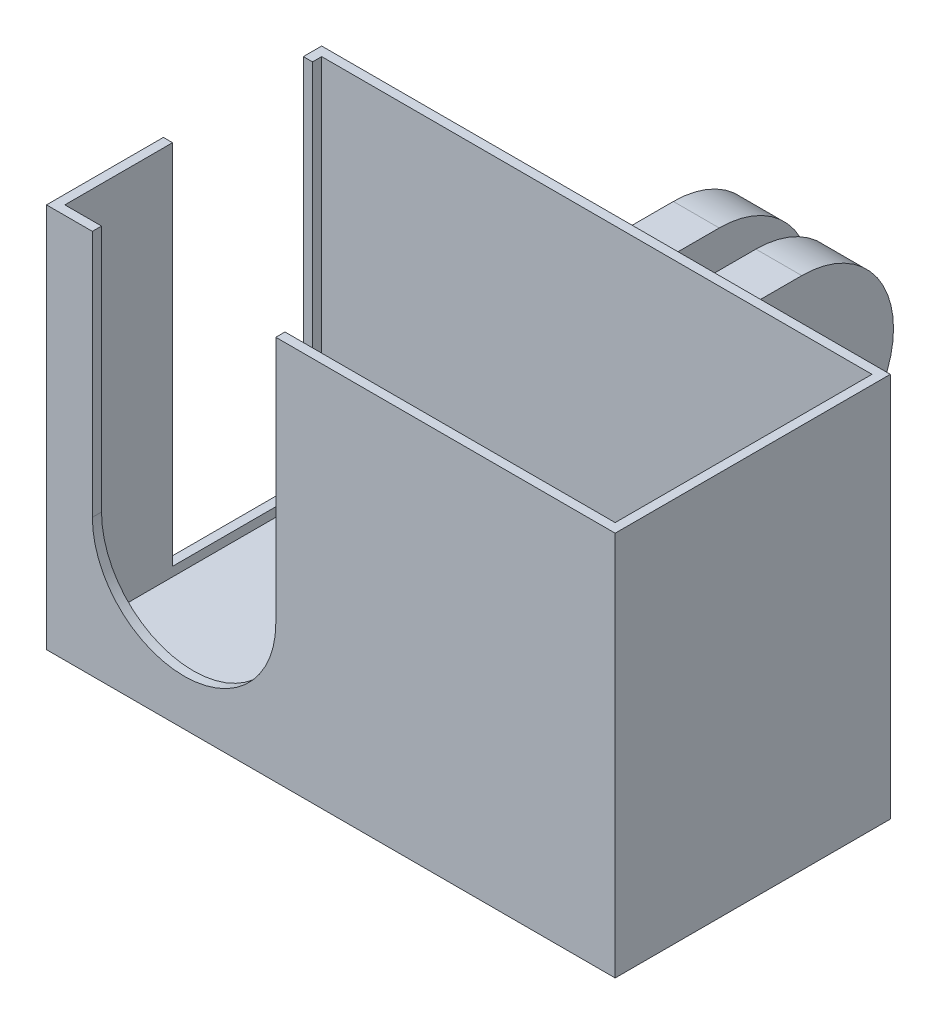
SolidWorks part; units mm, degrees
ref_plane "Front Plane" through (0, 0, 0) normal (0, 0, 1) x (1, 0, 0)
ref_plane "Top Plane" through (0, 0, 0) normal (0, 1, 0) x (1, 0, 0)
ref_plane "Right Plane" through (0, 0, 0) normal (1, 0, 0) x (0, 0, -1)
sketch "Sketch1" plane through (0, 0, 0) normal (0, 0, 1) x (1, 0, 0)
  line L1 (-30.3462, 18.505) -> (31.6538, 18.505)
  line L2 (-30.3462, 18.505) -> (-30.3462, -23.495)
  line L3 (-30.3462, -23.495) -> (31.6538, -23.495)
  line L4 (31.6538, 18.505) -> (31.6538, -23.495)
  dimension "D1" = 62
  dimension "D2" = 42
extrude "Boss-Extrude1" add sketch "Sketch1" along normal blind 30
sketch "Sketch2" plane through (0, 0, 30) normal (0, 0, 1) x (1, 0, 0)
  line L0 (-30.3462, -23.495) -> (31.6538, -23.495) construction
  line L1 (-30.3462, 18.505) -> (-30.3462, -23.495) construction
  circle A0 centre (-15.3462, -8.495) radius 10
  dimension "D1" = 15
  dimension "D2" = 20
  dimension "D3" = 15
extrude "Cut-Extrude1" cut sketch "Sketch2" against normal blind 6
sketch "Sketch3" plane through (0, 0, 30) normal (0, 0, 1) x (1, 0, 0)
  line L0 (-30.3462, 18.505) -> (-30.3462, -23.495) construction
  line L5 (-29.3462, 17.505) -> (30.6538, 17.505)
  line L6 (-29.3462, 17.505) -> (-29.3462, -22.495)
  line L7 (-29.3462, -22.495) -> (30.6538, -22.495)
  line L8 (30.6538, 17.505) -> (30.6538, -22.495)
  line L9 (31.6538, -23.495) -> (31.6538, 18.505) construction
  line L10 (31.6538, 18.505) -> (-30.3462, 18.505) construction
  line L11 (-30.3462, -23.495) -> (31.6538, -23.495) construction
  dimension "D1" = 1
  dimension "D2" = 1
  dimension "D3" = 1
  dimension "D4" = 1
extrude "Cut-Extrude2" cut sketch "Sketch3" against normal blind 27 from offset 2 offset against normal yes
sketch "Sketch4" plane through (0, 18.505, 0) normal (0, 1, 0) x (1, 0, 0)
  line L0 (-30.3462, -30) -> (-30.3462, 0) construction
  line L1 (-29.3462, -1) -> (30.6538, -1)
  line L2 (-29.3462, -1) -> (-29.3462, -29)
  line L3 (-29.3462, -29) -> (30.6538, -29)
  line L4 (30.6538, -1) -> (30.6538, -29)
  line L5 (31.6538, -30) -> (31.6538, 0) construction
  line L6 (-55, 0) -> (55, 0) construction
  line L7 (31.6538, -30) -> (-30.3462, -30) construction
  dimension "D1" = 1
  dimension "D2" = 1
  dimension "D3" = 1
  dimension "D4" = 1
extrude "Cut-Extrude3" cut sketch "Sketch4" against normal up to surface (41 mm away) up to face at (0.6538, -22.495, 14.5)
sketch "Sketch5" plane through (0, 18.505, 0) normal (0, 1, 0) x (1, 0, 0)
  line L0 (-29.3462, -29) -> (30.6538, -29) construction
  line L1 (-25.3462, -29) -> (-5.3462, -29)
  line L2 (-25.3462, -29) -> (-25.3462, -30)
  line L3 (-25.3462, -30) -> (-5.3462, -30)
  line L4 (-5.3462, -29) -> (-5.3462, -30)
  line L5 (31.6538, -30) -> (-30.3462, -30) construction
  line L6 (-30.3462, -30) -> (-30.3462, 0) construction
  dimension "D1" = 20
  dimension "D2" = 5
extrude "Cut-Extrude4" cut sketch "Sketch5" against normal blind 27
sketch "Sketch7" plane through (0, 0, 0) normal (1, 0, 0) x (0, 0, -1)
  line L1 (0, 7.9996) -> (15, 7.9996)
  line L2 (0, 7.9996) -> (0, -12.0004)
  line L3 (0, -12.0004) -> (15, -12.0004)
  arc A0 (15, 7.9996) -> (15, -12.0004) centre (15, -2.0004) cw
  point P5 (0, 0)
  dimension "D3" = 10
  dimension "D1" = 15
  dimension "D2" = 20
extrude "Boss-Extrude2" add sketch "Sketch7" along normal blind 5 from offset 2
sketch "Sketch8" plane through (0, 0, 0) normal (1, 0, 0) x (0, 0, -1)
  line L0 (0, -12.0004) -> (0, 7.9996)
  line L1 (0, 7.9996) -> (15, 7.9996)
  line L2 (0, -12.0004) -> (15, -12.0004)
  arc A0 (15, -12.0004) -> (15, 7.9996) centre (15, -2.0004) ccw
  point P6 (0, 0)
  dimension "D4" = 10
  dimension "D1" = 15
  dimension "D2" = 15
  dimension "D3" = 20
extrude "Boss-Extrude3" add sketch "Sketch8" against normal blind 5 from offset 2 offset against normal yes
sketch "Sketch10" plane through (-30.3462, 0, 0) normal (-1, 0, 0) x (0, 0, 1)
  line L2 (2, -21.495) -> (2, 18.505)
  line L3 (2, 18.505) -> (17.2555, 18.505)
  line L5 (30, 18.505) -> (0, 18.505) construction
  line L6 (17.2555, -21.495) -> (17.2555, 18.505)
  line L7 (0, 18.505) -> (0, -23.495) construction
  line L8 (2, -21.495) -> (17.2555, -21.495)
  line L9 (30, -23.495) -> (0, -23.495) construction
  dimension "D1" = 2
  dimension "D2" = 15.2555
  dimension "D3" = 2
extrude "Cut-Extrude5" cut sketch "Sketch10" against normal up to surface (1 mm away) up to face at (-29.3462, -1.995, 15)
